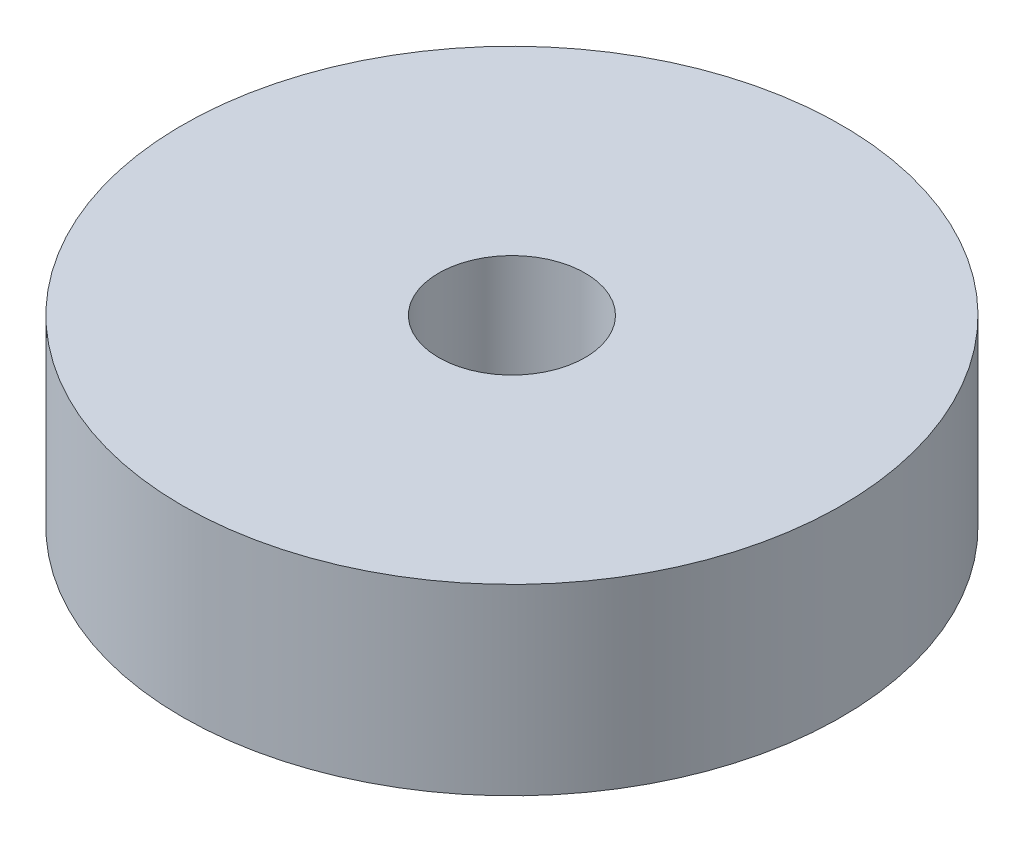
SolidWorks part; units mm, degrees
ref_plane "Front Plane" through (0, 0, 0) normal (0, 0, 1) x (1, 0, 0)
ref_plane "Top Plane" through (0, 0, 0) normal (0, 1, 0) x (1, 0, 0)
ref_plane "Right Plane" through (0, 0, 0) normal (1, 0, 0) x (0, 0, -1)
sketch "Sketch1" plane through (0, 0, 0) normal (0, 1, 0) x (1, 0, 0)
  circle A0 centre (0, 0) radius 14.2875
  circle A1 centre (0, 0) radius 3.175
extrude "Boss-Extrude1" add sketch "Sketch1" along normal blind 7.9375
